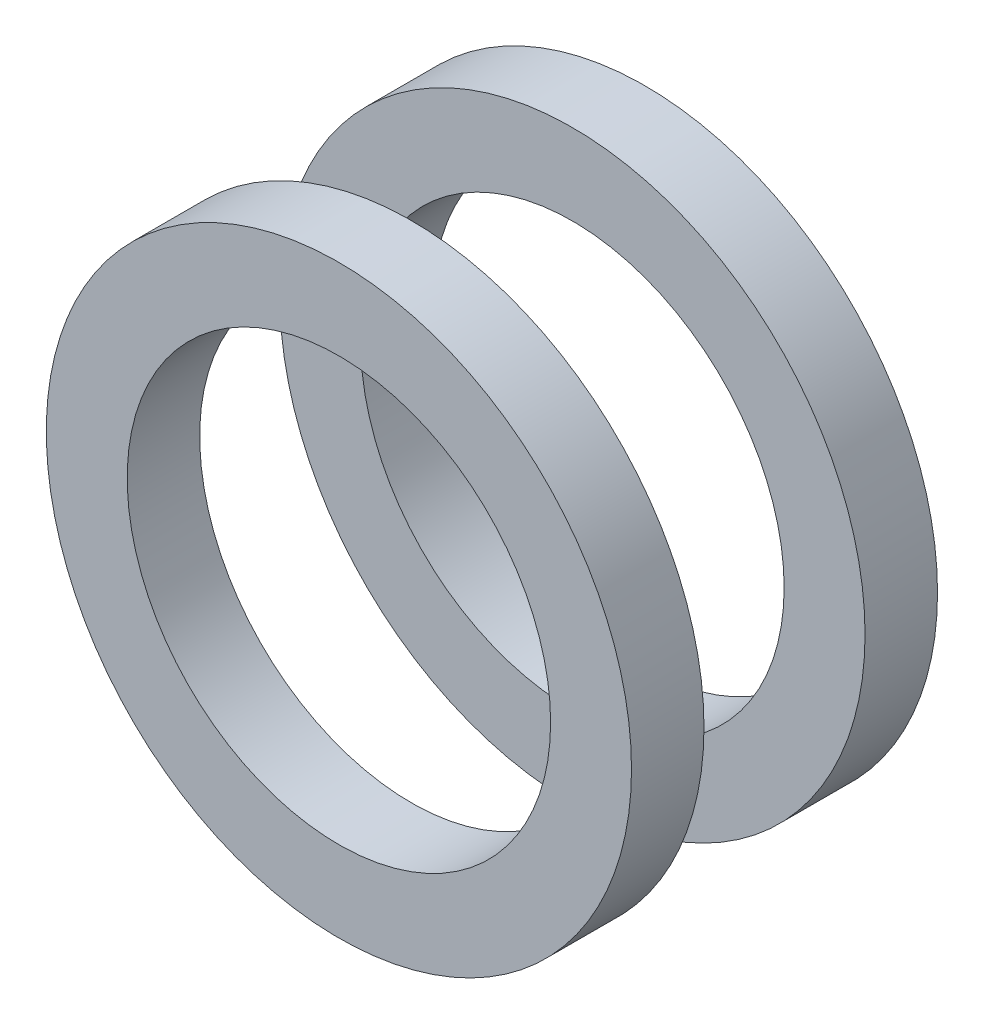
SolidWorks part; units mm, degrees
ref_plane "Спереди" through (0, 0, 0) normal (0, 0, 1) x (1, 0, 0)
ref_plane "Сверху" through (0, 0, 0) normal (0, 1, 0) x (1, 0, 0)
ref_plane "Справа" through (0, 0, 0) normal (1, 0, 0) x (0, 0, -1)
sketch "Эскиз1" plane through (0, 0, 0) normal (0, 0, 1) x (1, 0, 0)
  circle A0 centre (0, 0) radius 72.6692
  circle A1 centre (0, 0) radius 52.5769
extrude "Endturn_R" add sketch "Эскиз1" along normal blind 18 from offset 20 separate body
sketch "Эскиз2" plane through (0, 0, 0) normal (0, 0, 1) x (1, 0, 0)
  circle A0 centre (0, 0) radius 72.6692
  circle A1 centre (0, 0) radius 52.5769
extrude "Endturn_L" add sketch "Эскиз2" along normal blind 18 from offset 38 separate body
